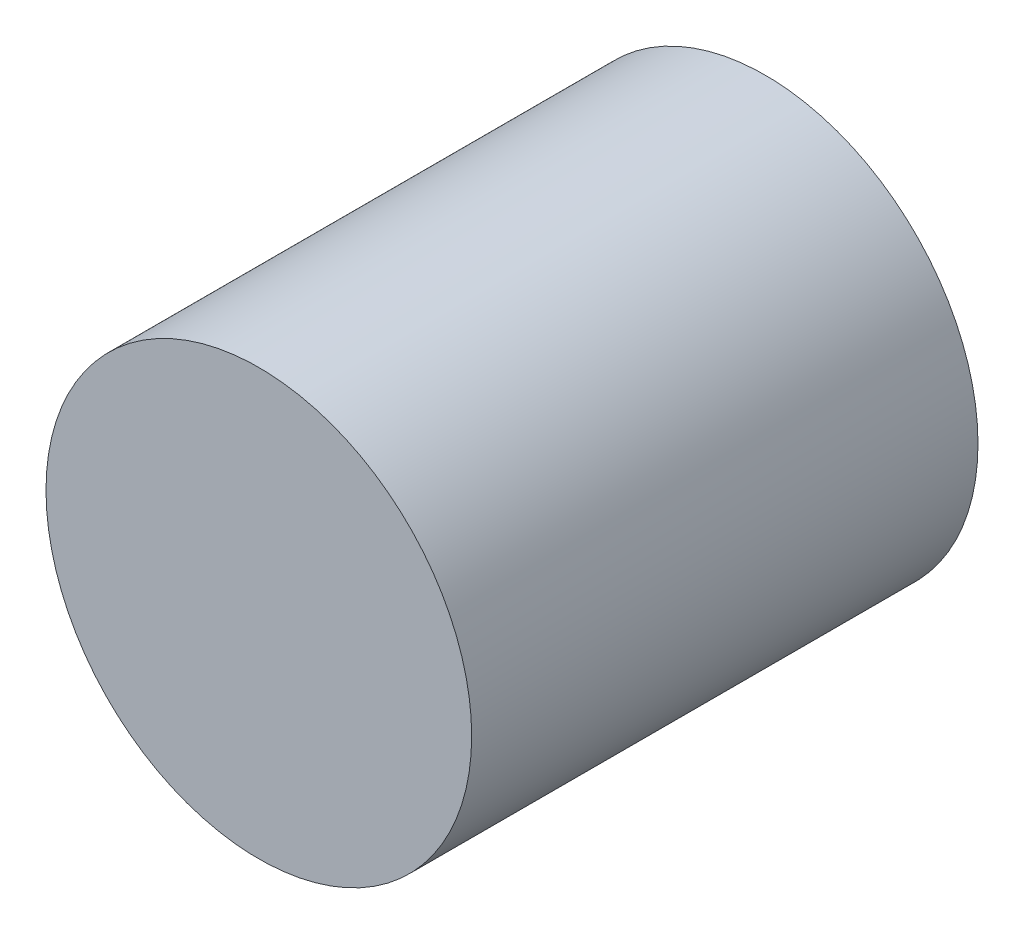
SolidWorks part; units mm, degrees
material "Pin material"
ref_plane "Front Plane" through (0, 0, 0) normal (0, 0, 1) x (1, 0, 0)
ref_plane "Top Plane" through (0, 0, 0) normal (0, 1, 0) x (1, 0, 0)
ref_plane "Right Plane" through (0, 0, 0) normal (1, 0, 0) x (0, 0, -1)
sketch "Sketch2" plane through (0, 0, 0) normal (0, 0, 1) x (1, 0, 0)
  circle A0 centre (0, 0) radius 5.7
extrude "Boss-Extrude2" add sketch "Sketch2" along normal blind 13.56
